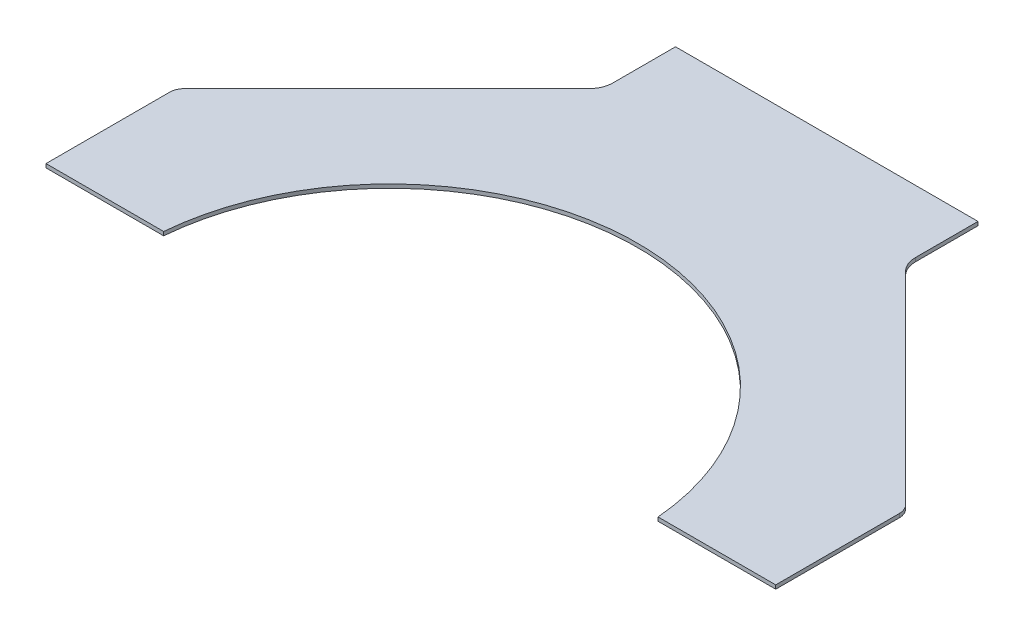
SolidWorks part; units mm, degrees
ref_plane "Front" through (0, 0, 0) normal (0, 0, 1) x (1, 0, 0)
ref_plane "Top" through (0, 0, 0) normal (0, 1, 0) x (1, 0, 0)
ref_plane "Right" through (0, 0, 0) normal (1, 0, 0) x (0, 0, -1)
sketch "Sketch1" plane through (0, 0, 0) normal (0, 1, 0) x (1, 0, 0)
  line L0 (-19.3, 1.125) -> (-13.0767, 1.125)
  line L1 (13.0767, 1.125) -> (19.3, 1.125)
  line L2 (19.3, 1.125) -> (19.3, 7.663)
  line L3 (19.0657, 8.2286) -> (8.3661, 18.9282)
  line L4 (8, 19.8121) -> (8, 23.125)
  line L5 (8, 23.125) -> (-8, 23.125)
  line L6 (-8, 23.125) -> (-8, 19.8121)
  line L7 (-8.3661, 18.9282) -> (-19.0657, 8.2286)
  line L8 (-19.3, 7.663) -> (-19.3, 1.125)
  line L9 (0, 23.125) -> (0, 0) construction
  line L10 (0, 0) -> (25.5154, 0) construction
  arc A0 (-13.0767, 1.125) -> (13.0767, 1.125) centre (0, 0) cw
  arc A1 (19.3, 7.663) -> (19.0657, 8.2286) centre (18.5, 7.663) ccw
  arc A2 (8.3661, 18.9282) -> (8, 19.8121) centre (9.25, 19.8121) cw
  arc A3 (-8, 19.8121) -> (-8.3661, 18.9282) centre (-9.25, 19.8121) cw
  arc A4 (-19.0657, 8.2286) -> (-19.3, 7.663) centre (-18.5, 7.663) ccw
  dimension "D1" = 13.125
  dimension "D7" = 0.8
  dimension "D8" = 1.25
  dimension "D2" = 23.125
  dimension "D3" = 16
  dimension "D4" = 1.125
  dimension "D5" = 38.6
  dimension "D6" = 45
  dimension "D9" = 19.3
extrude "Boss-Extrude1" add sketch "Sketch1" against normal blind 0.2
